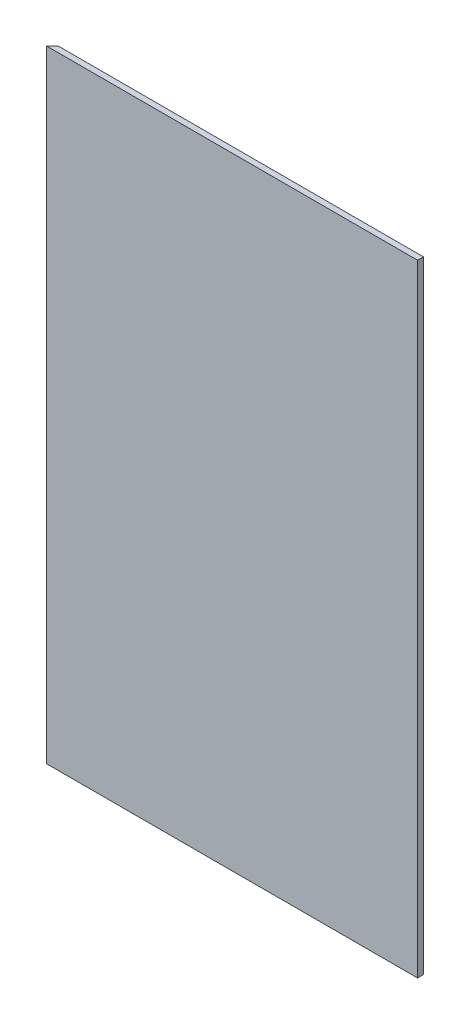
SolidWorks part; units mm, degrees
ref_plane "前视基准面" through (0, 0, 0) normal (0, 0, 1) x (1, 0, 0)
ref_plane "上视基准面" through (0, 0, 0) normal (0, 1, 0) x (1, 0, 0)
ref_plane "右视基准面" through (0, 0, 0) normal (1, 0, 0) x (0, 0, -1)
sketch "草图1" plane through (0, 0, 0) normal (0, 0, 1) x (1, 0, 0)
  line L1 (-95.5, 160) -> (95.5, 160)
  line L2 (-95.5, 160) -> (-95.5, -160)
  line L3 (-95.5, -160) -> (95.5, -160)
  line L4 (95.5, 160) -> (95.5, -160)
  line L5 (-95.5, 160) -> (95.5, -160) construction
  line L6 (-95.5, -160) -> (95.5, 160) construction
  point P0 (0, 0)
extrude "凸台-拉伸1" add sketch "草图1" along normal blind 3
sketch "草图4" plane through (0, 160, 0) normal (0, 1, 0) x (1, 0, 0)
  line L0 (-95.5, -3) -> (-95.5, 0)
  line L1 (-95.5, 0) -> (-92.5, 0)
  line L2 (95.5, 0) -> (-95.5, 0) construction
  line L3 (-92.5, 0) -> (-95.5, -3)
extrude "切除-拉伸4" cut sketch "草图4" against normal through all
